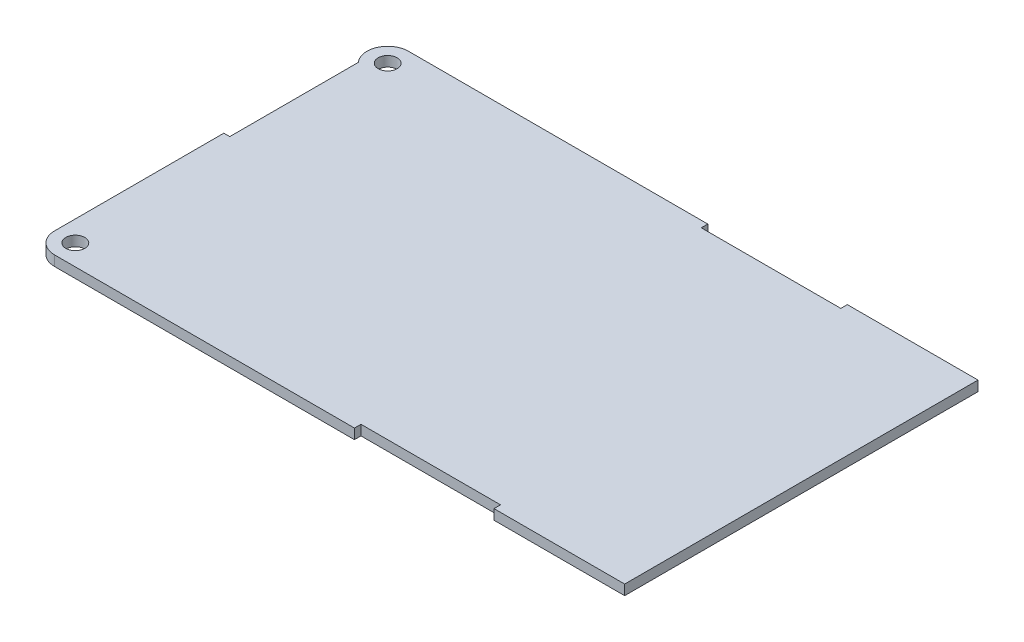
SolidWorks part; units mm, degrees
ref_plane "Front Plane" through (0, 0, 0) normal (0, 0, 1) x (1, 0, 0)
ref_plane "Top Plane" through (0, 0, 0) normal (0, 1, 0) x (1, 0, 0)
ref_plane "Right Plane" through (0, 0, 0) normal (1, 0, 0) x (0, 0, -1)
sketch "Sketch1" plane through (0, 0, 0) normal (0, 1, 0) x (1, 0, 0)
  line L0 (77.5, 59.5) -> (77.5, 0) construction
  line L1 (3.5, 0) -> (54, 0)
  line L2 (0, 3.5) -> (0, 32)
  line L3 (3.5, 59.5) -> (54, 59.5)
  line L4 (99.5, 0) -> (99.5, 59.5)
  line L5 (54, 59.5) -> (54, 0) construction
  line L6 (77.5, 58.4) -> (54, 58.4) construction
  line L7 (77.5, 1.1) -> (54, 1.1) construction
  line L8 (54, 0) -> (54, 1.1)
  line L9 (54, 1.1) -> (77.5, 1.1)
  line L10 (77.5, 1.1) -> (77.5, 0)
  line L11 (77.5, 0) -> (99.5, 0)
  line L12 (77.5, 59.5) -> (77.5, 58.4)
  line L13 (77.5, 58.4) -> (54, 58.4)
  line L14 (54, 58.4) -> (54, 59.5)
  line L15 (77.5, 59.5) -> (99.5, 59.5)
  line L16 (-8.5176, 32) -> (1, 32) construction
  line L17 (1, 61.8165) -> (1, 32) construction
  line L18 (1, 53.6569) -> (1, 32)
  line L19 (1, 32) -> (0, 32)
  arc A0 (3.5, 0) -> (0, 3.5) centre (3.5, 3.5) cw
  circle A2 centre (3.6, 56) radius 1.6
  circle A3 centre (3.5, 3.5) radius 1.6
  arc A4 (3.6, 59.5) -> (1, 53.6569) centre (3.6, 56) ccw
  point P15 (0, 0)
  point P18 (0, 59.5)
  dimension "D7" = 3.5
  dimension "D8" = 3.5
  dimension "D10" = 3.2
  dimension "D11" = 3.2
  dimension "D15" = 1
  dimension "D9" = 2.6
  dimension "D1" = 59.5
  dimension "D2" = 22
  dimension "D3" = 23.5
  dimension "D4" = 99.5
  dimension "D5" = 1.1
  dimension "D6" = 1.1
  dimension "D14" = 27.5
extrude "Boss-Extrude1" add sketch "Sketch1" along normal blind 1.7 contours L3 A4 L18 L19 L2 A0 L1 L8 L9 L10 L11 L4 L15 L12 L13 L14 A2 A3
